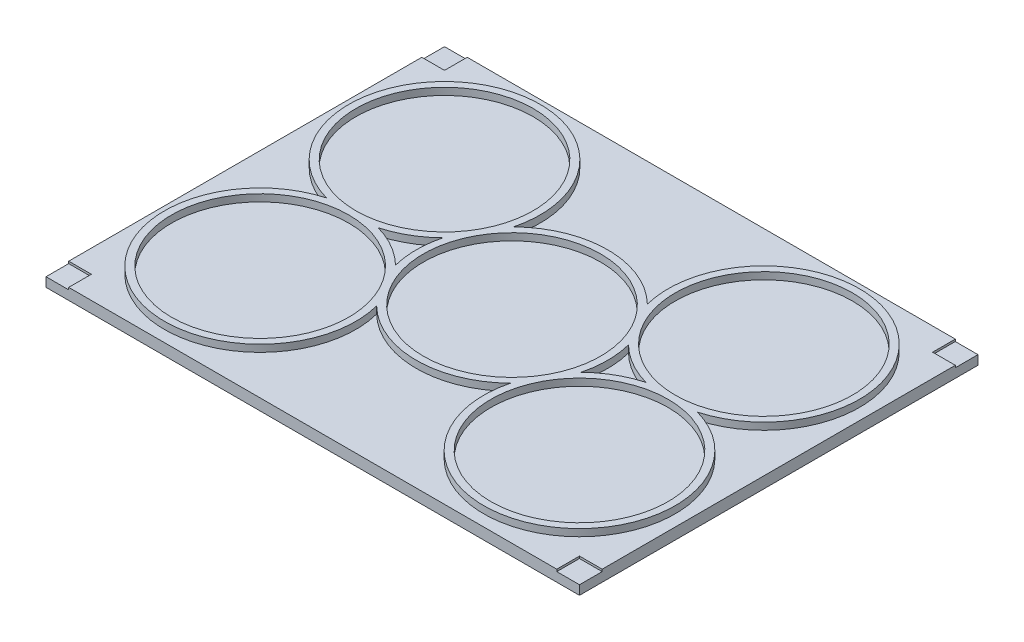
SolidWorks part; units mm, degrees
ref_plane "Front Plane" through (0, 0, 0) normal (0, 0, 1) x (1, 0, 0)
ref_plane "Top Plane" through (0, 0, 0) normal (0, 1, 0) x (1, 0, 0)
ref_plane "Right Plane" through (0, 0, 0) normal (1, 0, 0) x (0, 0, -1)
sketch "Sketch1" plane through (0, 0, 0) normal (0, 1, 0) x (1, 0, 0)
  line L0 (-49.789, -33.7297) -> (25.4443, -33.7297)
  line L1 (-49.789, -33.7297) -> (-49.789, 22.4703)
  line L2 (-49.789, 22.4703) -> (25.4443, 22.4703)
  line L3 (25.4443, -33.7297) -> (25.4443, 22.4703)
extrude "Boss-Extrude1" add sketch "Sketch1" along normal blind 1.6
sketch "Sketch2" plane through (0, 1.6, 0) normal (0, 1, 0) x (1, 0, 0)
  circle A0 centre (10.3443, 7.3703) radius 12.5
  circle A1 centre (10.3443, 7.3703) radius 13.5
  circle A2 centre (10.3443, -18.6297) radius 12.5
  circle A3 centre (10.3443, -18.6297) radius 13.5
  circle A4 centre (-12.1724, -5.6297) radius 12.5
  circle A5 centre (-12.1724, -5.6297) radius 13.5
  circle A6 centre (-34.689, 7.3703) radius 12.5
  circle A7 centre (-34.689, 7.3703) radius 13.5
  circle A8 centre (-34.689, -18.6297) radius 12.5
  circle A9 centre (-34.689, -18.6297) radius 13.5
extrude "Boss-Extrude2" add sketch "Sketch2" along normal blind 1 contours A9 A6 A5 A7 | A7 A9 | A7 A9 A5 A8 | A9 A7 A5 A6 | A5 A9 A7 A8 | A5 A9 | A5 A7 | A9 A4 A7 A5 | A9 A5 A3 A4 | A7 A4 A1 A5 | A1 A5 | A3 A5 A1 A4 | A3 A5 | A5 A3 A1 A2 | A5 A2 A1 A3 | A1 A3 | A5 A1 A3 A0 | A5 A0 A3 A1
sketch "Sketch3" plane through (0, 1.6, 0) normal (0, 1, 0) x (1, 0, 0)
  line L1 (-49.789, -33.7297) -> (-46.589, -33.7297)
  line L2 (-49.789, -33.7297) -> (-49.789, -30.5297)
  line L3 (-49.789, -30.5297) -> (-46.589, -30.5297)
  line L4 (-46.589, -33.7297) -> (-46.589, -30.5297)
  line L5 (25.4443, -33.7297) -> (22.2443, -33.7297)
  line L6 (25.4443, -33.7297) -> (25.4443, -30.5297)
  line L7 (25.4443, -30.5297) -> (22.2443, -30.5297)
  line L8 (22.2443, -33.7297) -> (22.2443, -30.5297)
  line L9 (25.4443, 22.4703) -> (22.2443, 22.4703)
  line L10 (25.4443, 22.4703) -> (25.4443, 19.2703)
  line L11 (25.4443, 19.2703) -> (22.2443, 19.2703)
  line L12 (22.2443, 22.4703) -> (22.2443, 19.2703)
  line L13 (-49.789, 22.4703) -> (-46.589, 22.4703)
  line L14 (-49.789, 22.4703) -> (-49.789, 19.2703)
  line L15 (-49.789, 19.2703) -> (-46.589, 19.2703)
  line L16 (-46.589, 22.4703) -> (-46.589, 19.2703)
extrude "Cut-Extrude1" cut sketch "Sketch3" against normal blind 0.3
